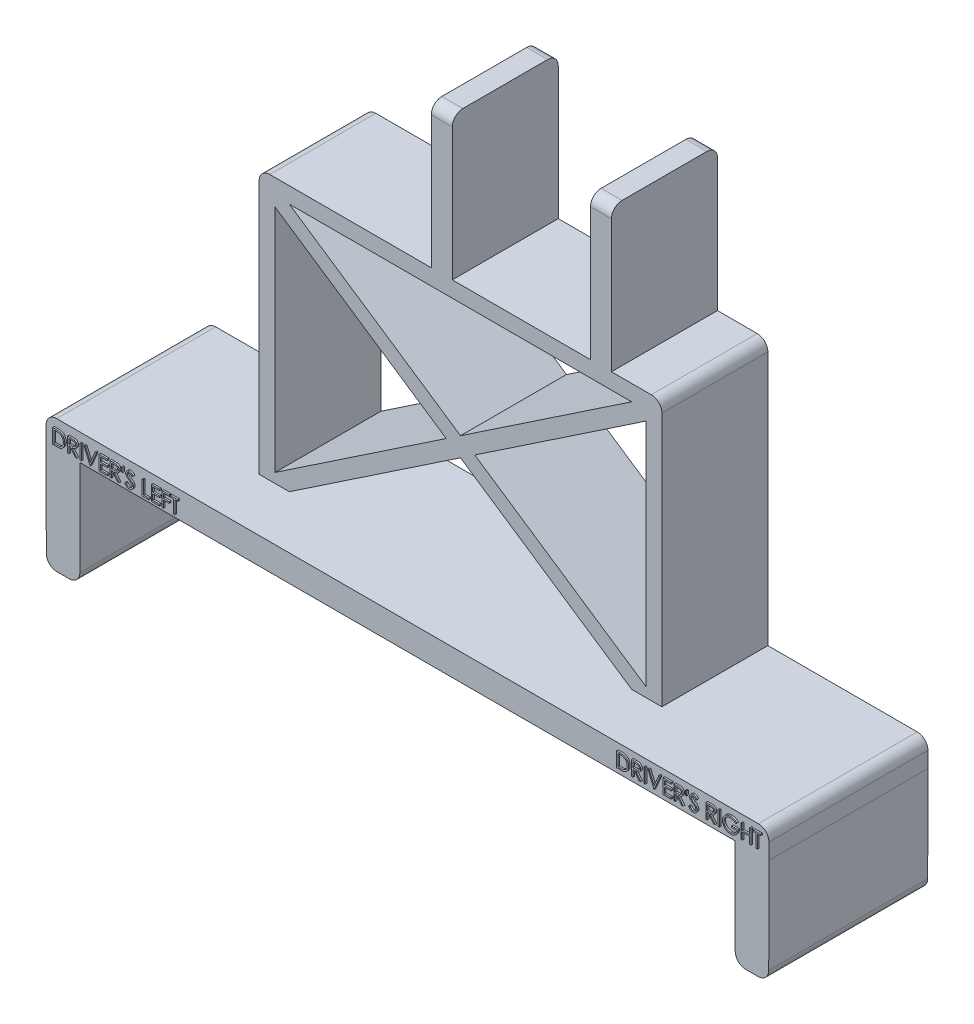
SolidWorks part; units mm, degrees
ref_plane "Front Plane" through (0, 0, 0) normal (0, 0, 1) x (1, 0, 0)
ref_plane "Top Plane" through (0, 0, 0) normal (0, 1, 0) x (1, 0, 0)
ref_plane "Right Plane" through (0, 0, 0) normal (1, 0, 0) x (0, 0, -1)
sketch "Sketch1" plane through (0, 0, 0) normal (0, 0, 1) x (1, 0, 0)
  line L12 (8.128, 0) -> (8.128, 25.4)
  line L13 (8.128, 0) -> (0, 0)
  line L24 (165.1, 0) -> (165.1, 25.4)
  line L30 (0, 31.75) -> (173.228, 31.75)
  line L32 (8.128, 25.4) -> (165.1, 25.4)
  line L33 (173.228, 31.75) -> (173.228, 0)
  line L34 (0, 31.75) -> (0, 1041.4108) construction
  line L37 (165.1, 0) -> (173.228, 0)
  line L38 (0, 31.75) -> (0, 0)
  dimension "D2" = 8.128
  dimension "D3" = 173.228
  dimension "D4" = 25.4
  dimension "D5" = 8.128
  dimension "D12" = 6.35
extrude "Boss-Extrude2" add sketch "Sketch1" along normal blind 38.1
sketch "Sketch7" plane through (0, 0, 0) normal (0, 0, 1) x (1, 0, 0)
  line L0 (86.614, 68.2701) -> (86.614, 42.7511) construction
  line L2 (173.228, 31.75) -> (0, 31.75) construction
  line L3 (173.228, 31.75) -> (0, 31.75) construction
  line L6 (38.354, 95.25) -> (38.354, 31.75)
  line L7 (38.354, 31.75) -> (42.164, 31.75)
  line L8 (134.874, 95.25) -> (134.874, 31.75)
  line L9 (38.354, 95.25) -> (134.874, 95.25)
  line L13 (42.164, 31.75) -> (42.164, 91.44)
  line L14 (131.064, 91.44) -> (131.064, 31.75)
  line L15 (42.164, 91.44) -> (131.064, 91.44)
  line L16 (131.064, 31.75) -> (134.874, 31.75)
  point P4 (86.614, 31.75)
  point P15 (86.614, 95.25)
  dimension "D2" = 3.81
  dimension "D3" = 63.5
  dimension "D4" = 44.45
  dimension "D5" = 3.81
extrude "Boss-Extrude6" add sketch "Sketch7" along normal blind 25.4
sketch "Sketch6" plane through (0, 95.25, 0) normal (0, 1, 0) x (1, 0, 0)
  line L26 (134.874, 0) -> (38.354, 0) construction
  line L30 (79.6112, 0) -> (79.6112, -25.4)
  line L31 (79.6112, -25.4) -> (84.6912, -25.4)
  line L32 (84.6912, 0) -> (84.6912, -25.4)
  line L33 (79.6112, 0) -> (84.6912, 0)
  line L34 (117.7112, 0) -> (117.7112, -25.4)
  line L35 (117.7112, -25.4) -> (122.7912, -25.4)
  line L36 (122.7912, 0) -> (122.7912, -25.4)
  line L37 (117.7112, 0) -> (122.7912, 0)
  line L46 (134.874, -25.4) -> (38.354, -25.4) construction
  line L51 (0, -38.1) -> (0, 0) construction
  point P32 (117.7112, -12.7)
  dimension "D2" = 84.6912
  dimension "D5" = 5.08
  dimension "D6" = 5.08
  dimension "D15" = 33.02
extrude "Boss-Extrude5" add sketch "Sketch6" along normal blind 34.29
fillet "Fillet1" radius 2.54 8 edges at (120.2512, 129.54, 0) (82.1512, 129.54, 0) (120.2512, 129.54, 25.4) (82.1512, 129.54, 25.4) (173.228, 31.75, 19.05) (134.874, 95.25, 12.7) (0, 31.75, 19.05) (38.354, 95.25, 12.7)
sketch "Sketch11" plane through (0, 0, 0) normal (0, 0, 1) x (1, 0, 0)
  line L0 (42.164, 89.1454) -> (83.1966, 61.595)
  line L3 (127.6466, 31.75) -> (131.064, 31.75)
  line L4 (131.064, 31.75) -> (131.064, 34.0446)
  line L5 (131.064, 91.44) -> (131.064, 31.75) construction
  line L6 (131.064, 34.0446) -> (90.0314, 61.595)
  line L8 (45.5814, 91.44) -> (42.164, 91.44)
  line L9 (42.164, 91.44) -> (42.164, 89.1454)
  line L10 (127.6466, 91.44) -> (131.064, 91.44)
  line L11 (131.064, 91.44) -> (131.064, 89.1454)
  line L12 (131.064, 89.1454) -> (90.0314, 61.595)
  line L13 (45.5814, 31.75) -> (42.164, 31.75)
  line L14 (42.164, 31.75) -> (42.164, 34.0446)
  line L15 (42.164, 34.0446) -> (83.1966, 61.595)
  line L16 (42.164, 31.75) -> (131.064, 91.44) construction
  line L17 (42.164, 91.44) -> (131.064, 31.75) construction
  line L18 (86.614, 59.3004) -> (45.5814, 31.75)
  line L19 (86.614, 59.3004) -> (127.6466, 31.75)
  line L20 (86.614, 63.8896) -> (127.6466, 91.44)
  line L21 (86.614, 63.8896) -> (45.5814, 91.44)
  line L23 (42.164, 31.75) -> (42.164, 91.44) construction
  line L24 (42.164, 91.44) -> (131.064, 91.44) construction
  line L25 (170.688, 31.75) -> (2.54, 31.75) construction
  dimension "D1" = 3.81
  dimension "D2" = 3.81
extrude "Boss-Extrude7" add sketch "Sketch11" along normal up to surface (25.4 mm away) up to face at (93.0972, 87.5473, 25.4)
sketch "Sketch3" plane through (0, 0, 38.1) normal (0, 0, 1) x (1, 0, 0)
  line L2 (79.6112, 129.54) -> (84.6912, 129.54) construction
  line L8 (84.6912, 95.25) -> (84.6404, 95.25)
  line L9 (84.6912, 95.25) -> (84.6912, 129.54)
  line L10 (84.6912, 129.54) -> (84.6404, 129.54)
  line L11 (84.6404, 95.25) -> (84.6404, 129.54)
  line L12 (117.7112, 95.25) -> (117.762, 95.25)
  line L13 (117.7112, 95.25) -> (117.7112, 129.54)
  line L14 (117.7112, 129.54) -> (117.762, 129.54)
  line L15 (117.762, 95.25) -> (117.762, 129.54)
  line L41 (0, 25.4) -> (0.0508, 0)
  line L45 (0, 29.21) -> (0, 0) construction
  line L48 (0, 0) -> (8.128, 0) construction
  line L49 (0.0508, 0) -> (0, 0)
  line L50 (0, 0) -> (0, 25.4)
  line L51 (8.128, 25.4) -> (8.0772, 0)
  line L52 (8.0772, 0) -> (8.128, 0)
  line L53 (165.1, 0) -> (165.1, 25.4)
  line L54 (165.1, 25.4) -> (165.1508, 0)
  line L58 (165.1, 0) -> (173.228, 0) construction
  line L59 (165.1508, 0) -> (165.1, 0)
  line L91 (173.228, 25.4) -> (173.1772, 0)
  line L95 (173.228, 0) -> (173.228, 29.21) construction
  line L97 (173.1772, 0) -> (173.228, 0)
  line L99 (173.228, 0) -> (173.228, 25.4)
  line L101 (8.128, 25.4) -> (165.1, 25.4) construction
  line L129 (117.7112, 129.54) -> (122.7912, 129.54) construction
  line L130 (8.128, 25.4) -> (8.128, 0)
  dimension "D3" = 0.0508
  dimension "D2" = 0.0508
  dimension "D4" = 0.0508
  dimension "D5" = 0.0508
  dimension "D6" = 0.0508
  dimension "D1" = 0.0508
extrude "Clearance Trim" cut sketch "Sketch3" against normal up to surface (38.1 mm away)
fillet "Fillet2" radius 2.54 4 edges at (165.1508, 0, 19.05) (173.1772, 0, 19.05) (8.0772, 0, 19.05) (0.0508, 0, 19.05)
sketch "Sketch12" plane through (0, 0, 38.1) normal (0, 0, 1) x (1, 0, 0)
  text T0 "DRIVER'S RIGHT"
  text T1 "DRIVER'S LEFT\r\n"
extrude "Text" add sketch "Sketch12" along normal blind 0.4
